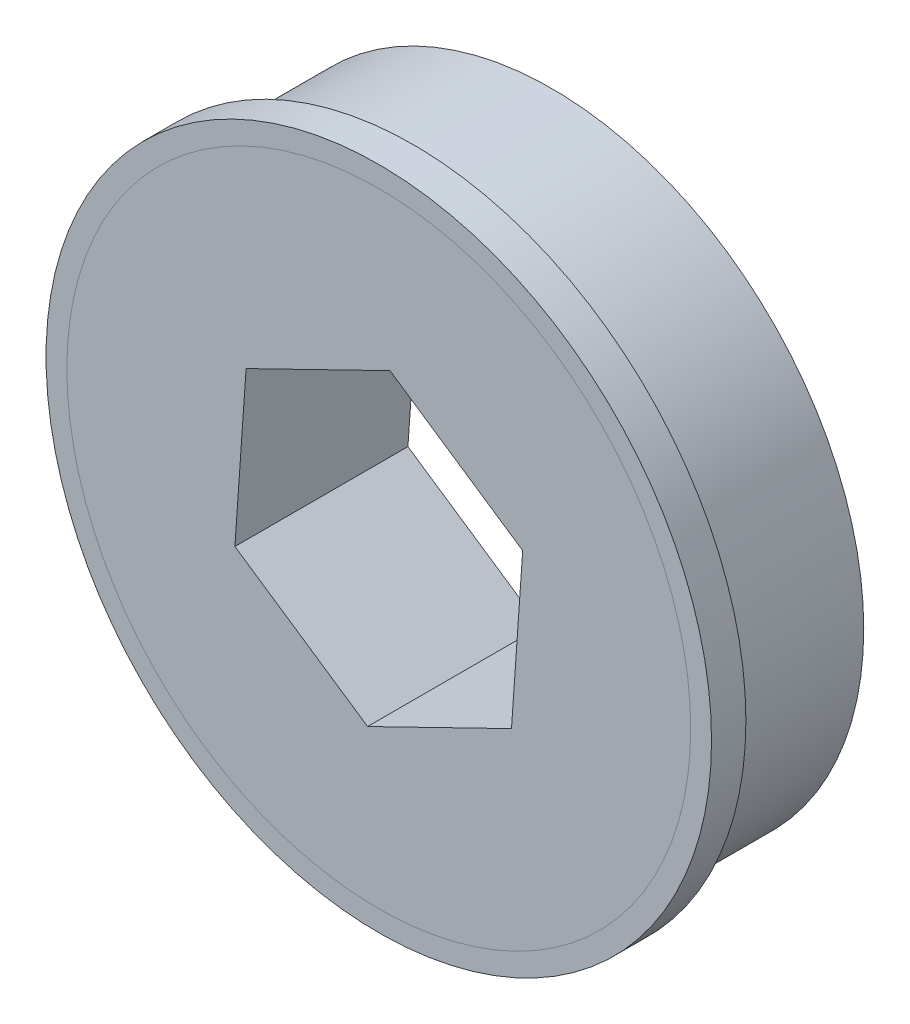
SolidWorks part; units mm, degrees
ref_plane "Front Plane" through (0, 0, 0) normal (0, 0, 1) x (1, 0, 0)
ref_plane "Top Plane" through (0, 0, 0) normal (0, 1, 0) x (1, 0, 0)
ref_plane "Right Plane" through (0, 0, 0) normal (1, 0, 0) x (0, 0, -1)
sketch "Sketch1" plane through (0, 0, 0) normal (0, 0, 1) x (1, 0, 0)
  circle A0 centre (0, 0) radius 14.2875
extrude "Boss-Extrude1" add sketch "Sketch1" along normal blind 7.9248
sketch "Sketch2" plane through (0, 0, 7.9248) normal (0, 0, 1) x (1, 0, 0)
  line L1 (6.5909, 3.213) -> (0.5129, 7.3144)
  line L2 (0.5129, 7.3144) -> (-6.078, 4.1014)
  line L3 (-6.078, 4.1014) -> (-6.5909, -3.213)
  line L4 (-6.5909, -3.213) -> (-0.5129, -7.3144)
  line L5 (-0.5129, -7.3144) -> (6.078, -4.1014)
  line L6 (6.078, -4.1014) -> (6.5909, 3.213)
  circle A0 centre (0, 0) radius 6.35 construction
  dimension "D1" = 12.7
extrude "Cut-Extrude1" cut sketch "Sketch2" against normal blind 7.9248
sketch "Sketch3" plane through (0, 0, 7.9248) normal (0, 0, 1) x (1, 0, 0)
  circle A0 centre (0, 0) radius 14.2875
  circle A1 centre (0, 0) radius 15.24
extrude "Boss-Extrude2" add sketch "Sketch3" against normal blind 1.5748 separate body
